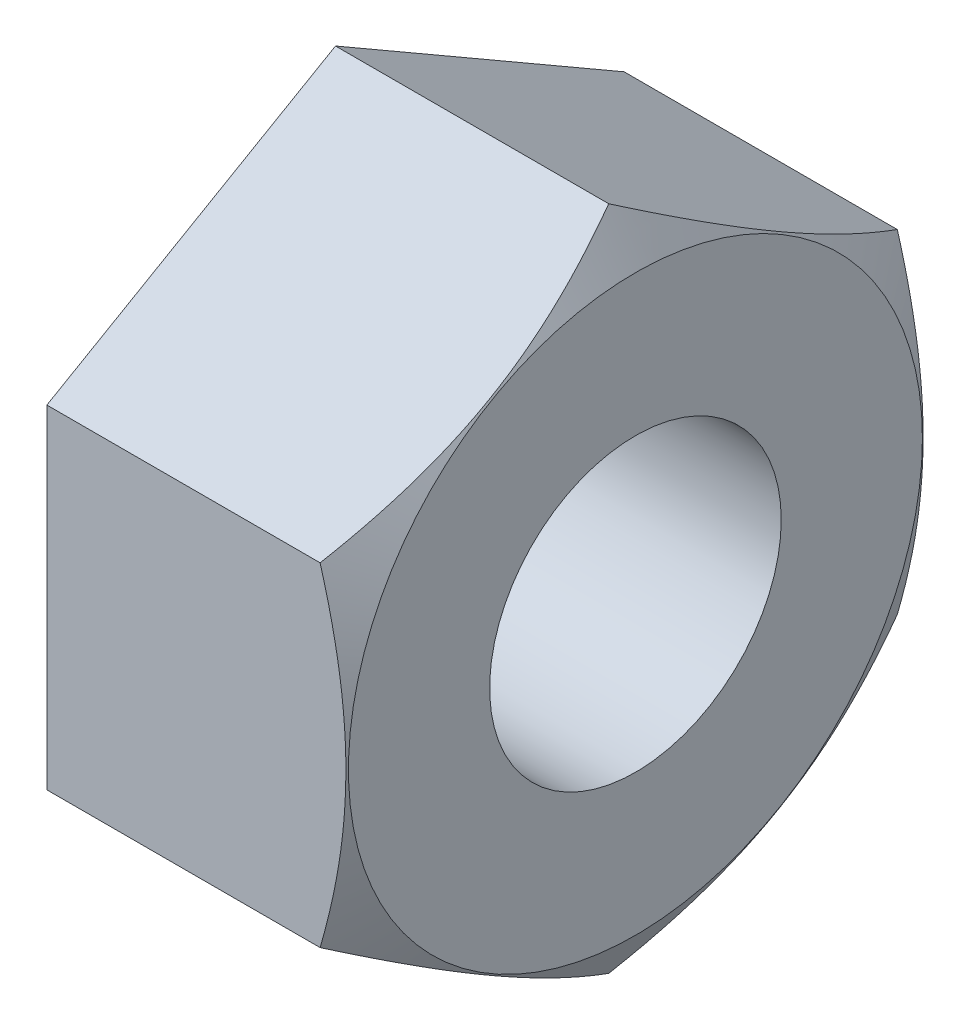
SolidWorks part; units mm, degrees
ref_plane "Front Plane" through (0, 0, 0) normal (0, 0, 1) x (1, 0, 0)
ref_plane "Top Plane" through (0, 0, 0) normal (0, 1, 0) x (1, 0, 0)
ref_plane "Right Plane" through (0, 0, 0) normal (1, 0, 0) x (0, 0, -1)
sketch "Sketch1" plane through (0, 0, 0) normal (1, 0, 0) x (0, 0, -1)
  line L1 (0, -24) -> (20.7846, -12)
  line L2 (20.7846, -12) -> (20.7846, 12)
  line L3 (20.7846, 12) -> (0, 24)
  line L4 (0, 24) -> (-20.7846, 12)
  line L5 (-20.7846, 12) -> (-20.7846, -12)
  line L6 (-20.7846, -12) -> (0, -24)
  circle A0 centre (0, 0) radius 20.7846 construction
  dimension "D1" = 24
extrude "Boss-Extrude1" add sketch "Sketch1" along normal blind 21.6
sketch "Sketch2" plane through (21.6, 0, 0) normal (1, 0, 0) x (0, 0, -1)
  circle A2 centre (0, 0) radius 20.6671
extrude "Cut-Extrude2" cut sketch "Sketch2" against normal blind 21.6 draft 60 flip side to cut
hole_wizard "M24 Tapped Hole1" positions "Sketch5" profile "Sketch6" tap size "M24" standard "ISO" end condition through all
sketch "Sketch5" plane through (21.6, 0, 0) normal (1, 0, 0) x (0, 0, -1)
  point P0 (0, 0)
  point P3 (0, 0)
  point P6 (0, 0)
sketch "Sketch6" plane through (21.6, 0, 0) normal (0, 1, 0) x (0, 0, -1)
  line L0 (0, 0) -> (0, 21.6)
  line L1 (0, 21.6) -> (10.5, 21.6)
  line L2 (10.5, 21.6) -> (10.5, 0)
  line L5 (10.5, 0) -> (0, 0)
  line L11 (0, -6.35) -> (0, 107.95) construction
  dimension "Thru Tap Drill Dia." = 21
  dimension "Thru Tap Drill Depth" = 21.6
cosmetic thread "Hole Thread1" parameters "D2"=24
cosmetic thread "Hole Thread2" parameters "D2"=24
cosmetic thread "Hole Thread3" parameters "D2"=24
